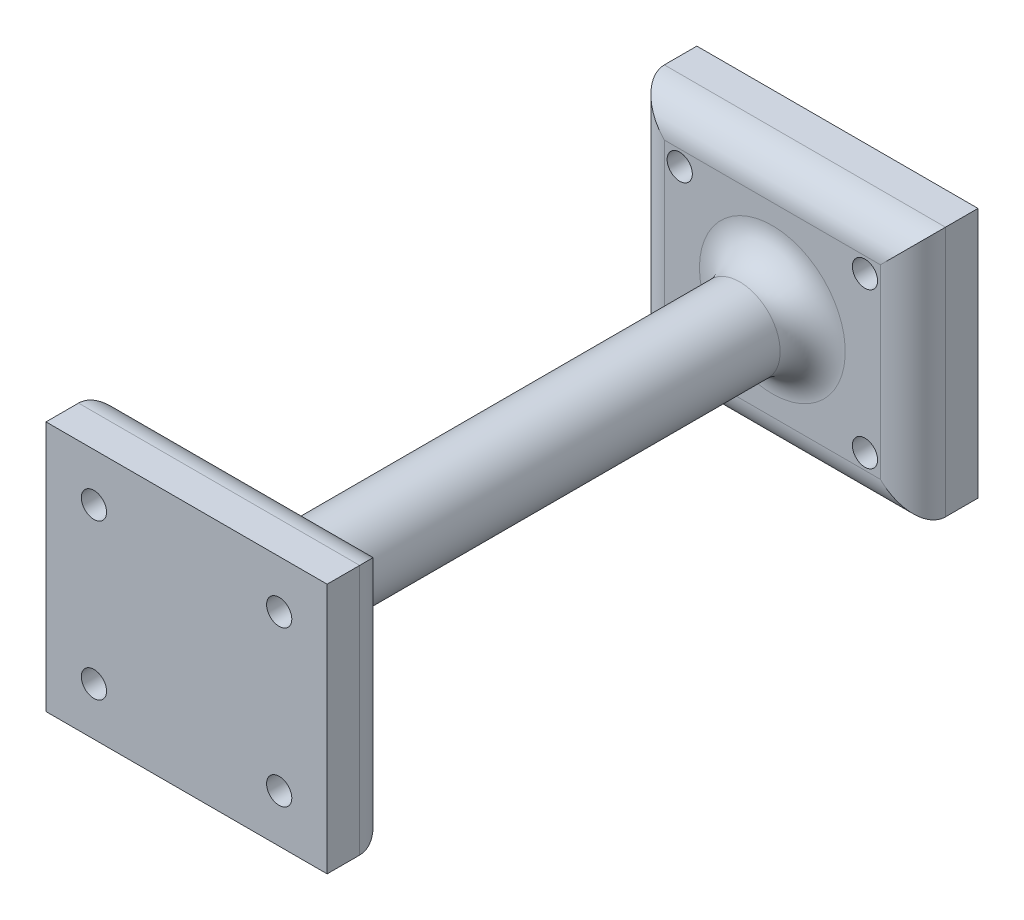
SolidWorks part; units mm, degrees
ref_plane "Front Plane" through (0, 0, 0) normal (0, 0, 1) x (1, 0, 0)
ref_plane "Top Plane" through (0, 0, 0) normal (0, 1, 0) x (1, 0, 0)
ref_plane "Right Plane" through (0, 0, 0) normal (1, 0, 0) x (0, 0, -1)
sketch "Sketch1" plane through (0, 0, 0) normal (0, 0, 1) x (1, 0, 0)
  line L0 (-91.7101, -330.2617) -> (-228.8418, -330.2617) construction
  line L1 (-113.3067, -293.2862) -> (-70.1135, -293.2862)
  line L2 (-113.3067, -293.2862) -> (-113.3067, -254.7355)
  line L3 (-113.3067, -254.7355) -> (-70.1135, -254.7355)
  line L4 (-70.1135, -293.2862) -> (-70.1135, -254.7355)
  line L5 (45.4216, -330.2617) -> (-91.7101, -330.2617) construction
  line L6 (-91.7101, -330.2617) -> (-91.7101, -274.0109) construction
  line L7 (-91.7101, -274.0109) -> (-91.7101, -302.1363) construction
  line L8 (-113.3067, -254.7355) -> (-70.1135, -293.2862) construction
  line L9 (-113.3067, -293.2862) -> (-70.1135, -254.7355) construction
  line L13 (45.4216, 53.4962) -> (45.4216, -445.0306) construction
  line L15 (-228.8418, -445.0306) -> (-228.8418, 53.4962) construction
extrude "Boss-Extrude1" add sketch "Sketch1" along normal blind 10
sketch "Sketch2" plane through (0, 0, 10) normal (0, 0, 1) x (1, 0, 0)
  line L0 (-113.3067, -274.0109) -> (-70.1135, -274.0109) construction
  line L1 (-113.3067, -254.7355) -> (-113.3067, -293.2862) construction
  line L2 (-70.1135, -293.2862) -> (-70.1135, -254.7355) construction
  circle A0 centre (-91.7101, -274.0109) radius 6.202
extrude "Boss-Extrude2" add sketch "Sketch2" along normal blind 79.85
sketch "Sketch3" plane through (0, 0, 100) normal (0, 0, -1) x (-1, 0, 0)
  line L4 (113.3067, -293.2862) -> (113.3067, -254.7355)
  line L5 (113.3067, -254.7355) -> (70.1135, -254.7355)
  line L6 (70.1135, -254.7355) -> (70.1135, -293.2862)
  line L7 (70.1135, -293.2862) -> (113.3067, -293.2862)
  line L8 (113.3067, -293.2862) -> (113.3067, -254.7355)
  line L9 (113.3067, -254.7355) -> (70.1135, -254.7355)
  line L10 (70.1135, -254.7355) -> (70.1135, -293.2862)
  line L11 (70.1135, -293.2862) -> (113.3067, -293.2862)
  dimension "D1" = 0
extrude "Boss-Extrude3" add sketch "Sketch3" along normal blind 10 separate body
fillet "Fillet2" radius 5 1 edges at (-85.5081, -274.0109, 10)
fillet "Fillet5" radius 5 4 edges at (-91.7101, -293.2862, 90) (-113.3067, -274.0109, 90) (-91.7101, -254.7355, 90) (-70.1135, -274.0109, 90)
fillet "Fillet6" radius 5 4 edges at (-113.3067, -274.0109, 10) (-91.7101, -254.7355, 10) (-91.7101, -293.2862, 10) (-70.1135, -274.0109, 10)
sketch "Sketch4" plane through (0, 0, 10) normal (0, 0, 1) x (1, 0, 0)
  line L0 (-70.1135, -254.7355) -> (-70.1135, -293.2862) construction
  line L1 (-70.1135, -293.2862) -> (-113.3067, -293.2862) construction
  line L2 (-91.7101, -293.2862) -> (-91.7101, -254.7355) construction
  line L3 (-70.1135, -293.2862) -> (-113.3067, -293.2862) construction
  line L4 (-113.3067, -254.7355) -> (-70.1135, -254.7355) construction
  line L5 (-113.3067, -274.0109) -> (-70.1135, -274.0109) construction
  line L6 (-113.3067, -293.2862) -> (-113.3067, -254.7355) construction
  line L7 (-70.1135, -254.7355) -> (-70.1135, -293.2862) construction
  circle A0 centre (-77.4795, -285.9202) radius 1.9371
  circle A2 centre (-105.9407, -285.9202) radius 1.9371
  circle A3 centre (-77.4795, -262.1015) radius 1.9371
  circle A4 centre (-105.9407, -262.1015) radius 1.9371
  dimension "D1" = 7.366
  dimension "D2" = 7.366
sketch "Sketch5" plane through (0, 0, 100) normal (0, 0, -1) x (-1, 0, 0)
  circle A0 centre (105.9407, -285.9202) radius 1.9371 construction
  circle A1 centre (105.9407, -262.1015) radius 1.9371 construction
  circle A2 centre (77.4795, -262.1015) radius 1.9371 construction
  circle A3 centre (77.4795, -285.9202) radius 1.9371 construction
  circle A4 centre (105.9407, -285.9202) radius 1.9371
  circle A5 centre (105.9407, -262.1015) radius 1.9371
  circle A6 centre (77.4795, -262.1015) radius 1.9371
  circle A7 centre (77.4795, -285.9202) radius 1.9371
extrude "Cut-Extrude3" cut sketch "Sketch5" along normal up to surface (10 mm away) up to face at (-91.7101, -274.0109, 90)
extrude "Cut-Extrude4" cut sketch "Sketch4" against normal up to surface (10 mm away) up to face at (-91.7101, -274.0109, 0)
sketch "Sketch6" plane through (0, 0, 100) normal (0, 0, 1) x (1, 0, 0)
  circle A0 centre (-77.4795, -262.1015) radius 1.9371 construction
  circle A1 centre (-105.9407, -262.1015) radius 1.9371 construction
  circle A2 centre (-77.4795, -285.9202) radius 1.9371 construction
  circle A3 centre (-105.9407, -285.9202) radius 1.9371 construction
  circle A4 centre (-77.4795, -262.1015) radius 1.9371
  circle A5 centre (-105.9407, -262.1015) radius 1.9371
  circle A6 centre (-77.4795, -285.9202) radius 1.9371
  circle A7 centre (-105.9407, -285.9202) radius 1.9371
